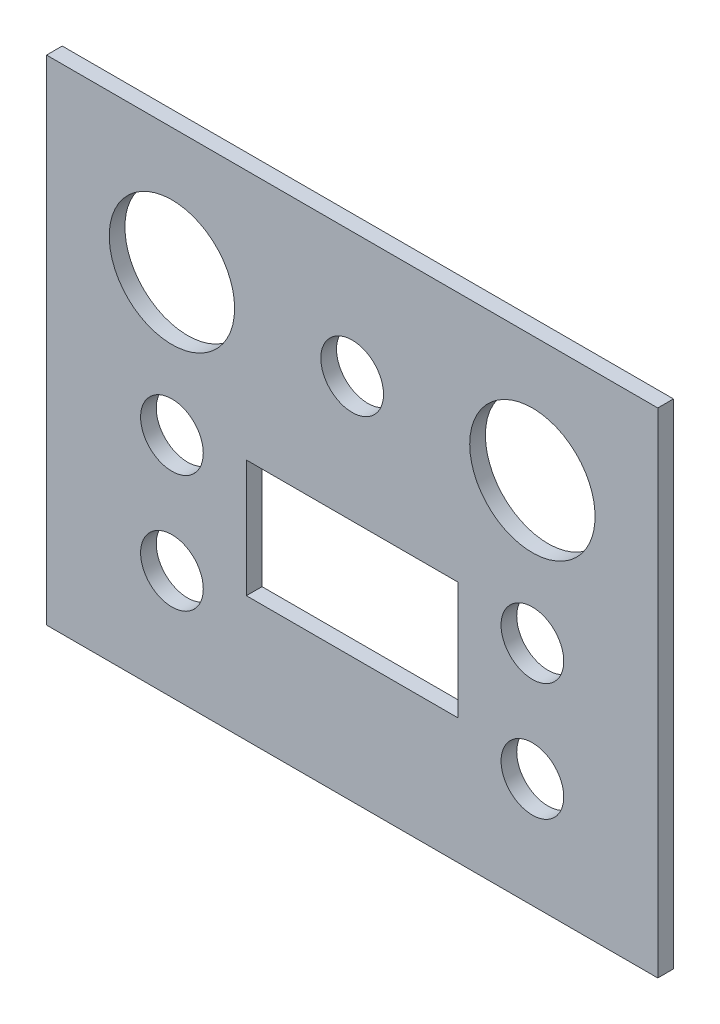
SolidWorks part; units mm, degrees
ref_plane "Спереди" through (0, 0, 0) normal (0, 0, 1) x (1, 0, 0)
ref_plane "Сверху" through (0, 0, 0) normal (0, 1, 0) x (1, 0, 0)
ref_plane "Справа" through (0, 0, 0) normal (1, 0, 0) x (0, 0, -1)
sketch "Sketch1" plane through (0, 0, 0) normal (0, 0, 1) x (1, 0, 0)
  line L0 (0, 0) -> (0, 50000) construction
  line L1 (-39, -31.5) -> (39, -31.5)
  line L2 (-39, -31.5) -> (-39, 31.5)
  line L3 (-39, 31.5) -> (39, 31.5)
  line L4 (39, -31.5) -> (39, 31.5)
  line L5 (-39, -31.5) -> (39, 31.5) construction
  line L6 (-39, 31.5) -> (39, -31.5) construction
  line L7 (0, 0) -> (50000, 0) construction
  line L8 (-23, -31.5) -> (-23, 49968.5) construction
  line L9 (-13.5, -0.5) -> (13.5, -0.5)
  line L10 (-13.5, -0.5) -> (-13.5, -15.5)
  line L11 (-13.5, -15.5) -> (13.5, -15.5)
  line L12 (13.5, -0.5) -> (13.5, -15.5)
  line L13 (0, -15.5) -> (0, -0.5) construction
  line L14 (-13.5, -8) -> (13.5, -8) construction
  line L15 (39, -17.5) -> (-49961, -17.5) construction
  line L17 (-13.5, 7.5) -> (13.5, 7.5) construction
  line L18 (-13.5, 7.5) -> (-13.5, -20.5) construction
  line L19 (-13.5, -20.5) -> (13.5, -20.5) construction
  line L20 (13.5, 7.5) -> (13.5, -20.5) construction
  line L21 (0, -20.5) -> (0, 7.5) construction
  line L22 (-13.5, -6.5) -> (13.5, -6.5) construction
  circle A0 centre (23, 15.5) radius 8
  circle A1 centre (23, 15.5) radius 11 construction
  circle A2 centre (0, 15.5) radius 6 construction
  circle A3 centre (0, 15.5) radius 4
  circle A4 centre (-23, -17.5) radius 6 construction
  circle A5 centre (-23, -17.5) radius 4
  circle A6 centre (23, -2.5) radius 4
  circle A7 centre (23, -2.5) radius 6 construction
  circle A8 centre (23, -17.5) radius 4
  circle A9 centre (23, -17.5) radius 6 construction
  circle A10 centre (-23, -2.5) radius 6 construction
  circle A11 centre (-23, -2.5) radius 4
  circle A12 centre (-23, 15.5) radius 11 construction
  circle A13 centre (-23, 15.5) radius 8
  point P0 (0, 0)
  point P8 (0, 31.5)
  point P11 (39, 0)
  point P147 (0, -6.5)
  point P172 (0, -8)
  dimension "D6" = 14
  dimension "D7" = 15
  dimension "D8" = 8
  dimension "D9" = 12
  dimension "D10" = 8
  dimension "D11" = 12
  dimension "D12" = 8
  dimension "D13" = 12
  dimension "D14" = 16
  dimension "D15" = 22
  dimension "D16" = 5
  dimension "D1" = 78
  dimension "D2" = 63
  dimension "D3" = 16
  dimension "D4" = 15
  dimension "D5" = 27
  dimension "D17" = 8
  dimension "D21" = 16
  dimension "D22" = 16
  dimension "D23" = 16
extrude "Boss-Extrude1" add sketch "Sketch1" along normal blind 2
